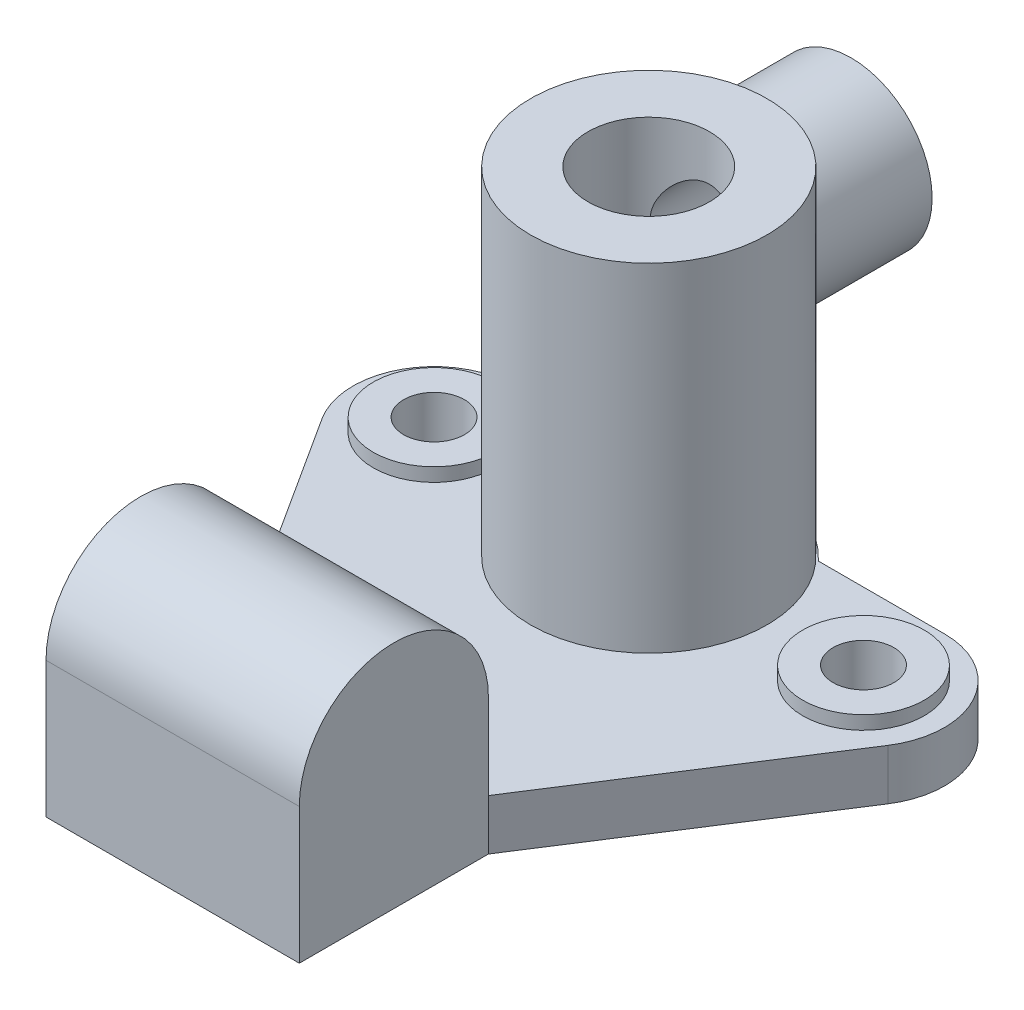
SolidWorks part; units mm, degrees
ref_plane "Front Plane" through (0, 0, 0) normal (0, 0, 1) x (1, 0, 0)
ref_plane "Top Plane" through (0, 0, 0) normal (0, 1, 0) x (1, 0, 0)
ref_plane "Right Plane" through (0, 0, 0) normal (1, 0, 0) x (0, 0, -1)
sketch "Sketch5" plane through (0, 0, 0) normal (0, 1, 0) x (1, 0, 0)
  line L0 (-37.5, -7.8763) -> (-83.7696, 64.1237)
  line L1 (-63.5792, 101.0987) -> (-26.201, 101.0987)
  line L2 (0, 0) -> (0, 57.9826) construction
  line L3 (63.5792, 101.0987) -> (26.201, 101.0987)
  line L4 (37.5, -7.8763) -> (83.7696, 64.1237)
  line L5 (-37.5, -7.8763) -> (37.5, -7.8763)
  arc A0 (-83.7696, 64.1237) -> (-63.5792, 101.0987) centre (-63.5792, 77.0987) cw
  arc A1 (83.7696, 64.1237) -> (63.5792, 101.0987) centre (63.5792, 77.0987) ccw
  arc A2 (-26.201, 101.0987) -> (26.201, 101.0987) centre (0, 77.0987) cw
  dimension "D1" = 24
  dimension "D4" = 35.5316
  dimension "D2" = 72
  dimension "D3" = 75
extrude "Boss-Extrude1" add sketch "Sketch5" along normal blind 15
sketch "Sketch7" plane through (0, 0, 0) normal (1, 0, 0) x (0, 0, -1)
  line L0 (-7.8763, 0) -> (-63.8763, 0)
  line L1 (-63.8763, 0) -> (-63.8763, 40.1903)
  line L2 (-7.8763, 40.1903) -> (-7.8763, 0)
  arc A0 (-63.8763, 40.1903) -> (-7.8763, 40.1903) centre (-35.8763, 40.1903) cw
  dimension "D1" = 56
  dimension "D2" = 40.1903
extrude "Boss-Extrude2" add sketch "Sketch7" along normal mid plane 75
sketch "Sketch8" plane through (0, 15, 0) normal (0, 1, 0) x (1, 0, 0)
  circle A3 centre (0, 77.0987) radius 35
  circle A5 centre (0, 77.0987) radius 18
  dimension "D3" = 70
  dimension "D6" = 36
extrude "Boss-Extrude13" add sketch "Sketch8" along normal blind 100
sketch "Sketch13" plane through (0, 15, 0) normal (0, 1, 0) x (1, 0, 0)
  circle A0 centre (0, 77.0987) radius 18
extrude "Cut-Extrude2" cut sketch "Sketch13" against normal blind 100
sketch "Sketch14" plane through (0, 15, 0) normal (0, 1, 0) x (1, 0, 0)
  circle A0 centre (-63.5792, 77.0987) radius 18
  circle A1 centre (63.5792, 77.0987) radius 18
  circle A2 centre (63.5792, 77.0987) radius 9
  circle A3 centre (-63.5792, 77.0987) radius 9
  dimension "D1" = 36
  dimension "D2" = 18
  dimension "D3" = 36
  dimension "D4" = 18
extrude "Boss-Extrude15" add sketch "Sketch14" along normal blind 4
sketch "Sketch15" plane through (0, 15, 0) normal (0, 1, 0) x (1, 0, 0)
  circle A0 centre (-63.5792, 77.0987) radius 9
  circle A1 centre (63.5792, 77.0987) radius 9
extrude "Cut-Extrude3" cut sketch "Sketch15" against normal blind 50
ref_plane "Plane1" through (0, 0, -137) normal (0, 0, 1) x (1, 0, 0)
sketch "Sketch18" plane through (0, 0, -137) normal (0, 0, 1) x (1, 0, 0)
  line L0 (-26.201, 0) -> (26.201, 0) construction
  circle A0 centre (0, 89) radius 24
  point P4 (0, 0)
  dimension "D1" = 48
  dimension "D2" = 89
  dimension "D3" = 89
extrude "Boss-Extrude16" add sketch "Sketch18" along normal up to next
sketch "Sketch19" plane through (0, 0, -137) normal (0, 0, -1) x (-1, 0, 0)
  circle A0 centre (0, 89) radius 12.5
  dimension "D1" = 25
extrude "Cut-Extrude4" cut sketch "Sketch19" against normal blind 50
sketch "Sketch20" [suppressed] plane through (37.5, 0, 0) normal (1, 0, 0) x (0, 0, -1)
  circle A0 centre (-35.8763, 40.1903) radius 14
  dimension "D1" = 28
extrude "Cut-Extrude5" [suppressed] cut sketch "Sketch20" against normal blind 100
sketch "Sketch50" [suppressed] plane through (0, 115, 0) normal (0, 1, 0) x (1, 0, 0)
  line L0 (-3.4245, 42.4505) -> (3.5755, 42.4505)
  dimension "D1" = 7
sketch "Sketch49" [suppressed] plane through (0, 0, 0) normal (1, 0, 0) x (0, 0, -1)
  line L0 (42.0987, 115) -> (-45.8677, 66.347)
  line L1 (42.0987, 115) -> (52.1701, 115)
  line L2 (112.0987, 115) -> (42.0987, 115) construction
  arc A1 (-7.8763, 40.1903) -> (-63.8763, 40.1903) centre (-35.8763, 40.1903) ccw construction
  dimension "D1" = 100.5247
rib "Rib78" [suppressed] sketch "Sketch49" sketch "Sketch49" thickness 10 extrusion direction parallel to sketch draft on no parameters "D1"=10
